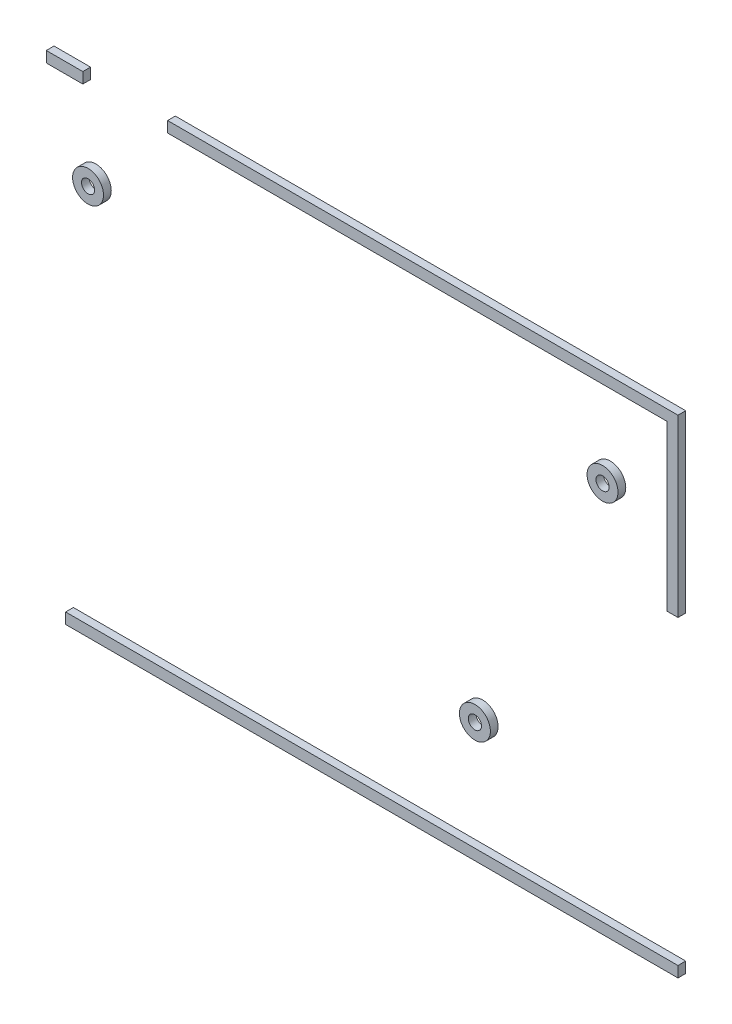
SolidWorks part; units mm, degrees
material "Custom Plastic"
ref_plane "Front Plane" through (0, 0, 0) normal (0, 0, 1) x (1, 0, 0)
ref_plane "Top Plane" through (0, 0, 0) normal (0, 1, 0) x (1, 0, 0)
ref_plane "Right Plane" through (0, 0, 0) normal (1, 0, 0) x (0, 0, -1)
sketch "Sketch1" plane through (0, 0, 0) normal (0, 0, 1) x (1, 0, 0)
  line L0 (44.0608, 63.2) -> (44.0608, 60.2) construction
  line L1 (17.7, -60.2) -> (176, -60.2)
  line L2 (17.7, -60.2) -> (17.7, -63)
  line L3 (17.7, -63) -> (176, -63)
  line L4 (176, -60.2) -> (176, -63)
  line L5 (173.2, 17.7) -> (176, 17.7)
  line L6 (173.2, 17.7) -> (173.2, 63)
  line L7 (173.2, 63) -> (176, 63)
  line L8 (176, 17.7) -> (176, 63)
  line L9 (173.2, 63) -> (44.0608, 63)
  line L10 (173.2, 63) -> (173.2, 60.2)
  line L11 (173.2, 60.2) -> (44.0608, 60.2)
  line L12 (44.0608, 63) -> (44.0608, 60.2)
  line L13 (44.0608, 60.2) -> (49.0608, 60.2) construction
  line L14 (22.1392, 63.2) -> (22.1392, 60.2) construction
  line L15 (12.7, 60.2) -> (22.1392, 60.2)
  line L16 (12.7, 60.2) -> (12.7, 63)
  line L17 (12.7, 63) -> (22.1392, 63)
  line L18 (22.1392, 60.2) -> (22.1392, 63)
  line L19 (176, 63) -> (-176, 63) construction
  circle A0 centre (123.5, -32) radius 4
  circle A1 centre (156.5, 38) radius 4
  circle A2 centre (23.5, 38) radius 4
  circle A3 centre (23.5, 38) radius 4 construction
  circle A4 centre (156.5, 38) radius 4 construction
  circle A5 centre (123.5, -32) radius 4 construction
  circle A6 centre (23.5, 38) radius 1.7
  circle A7 centre (156.5, 38) radius 1.7
  circle A8 centre (123.5, -32) radius 1.7
  dimension "D1" = 3.4
  dimension "D2" = 3.4
  dimension "D3" = 3.4
extrude "Boss-Extrude1" add sketch "Sketch1" along normal up to surface (2 mm away) contours L9 L12 L11 L6 | L15 L18 L17 L16 | A2 A6 | L5 L8 L7 L6 | A1 A7 | A0 A8 | L4 L1 L2 L3
